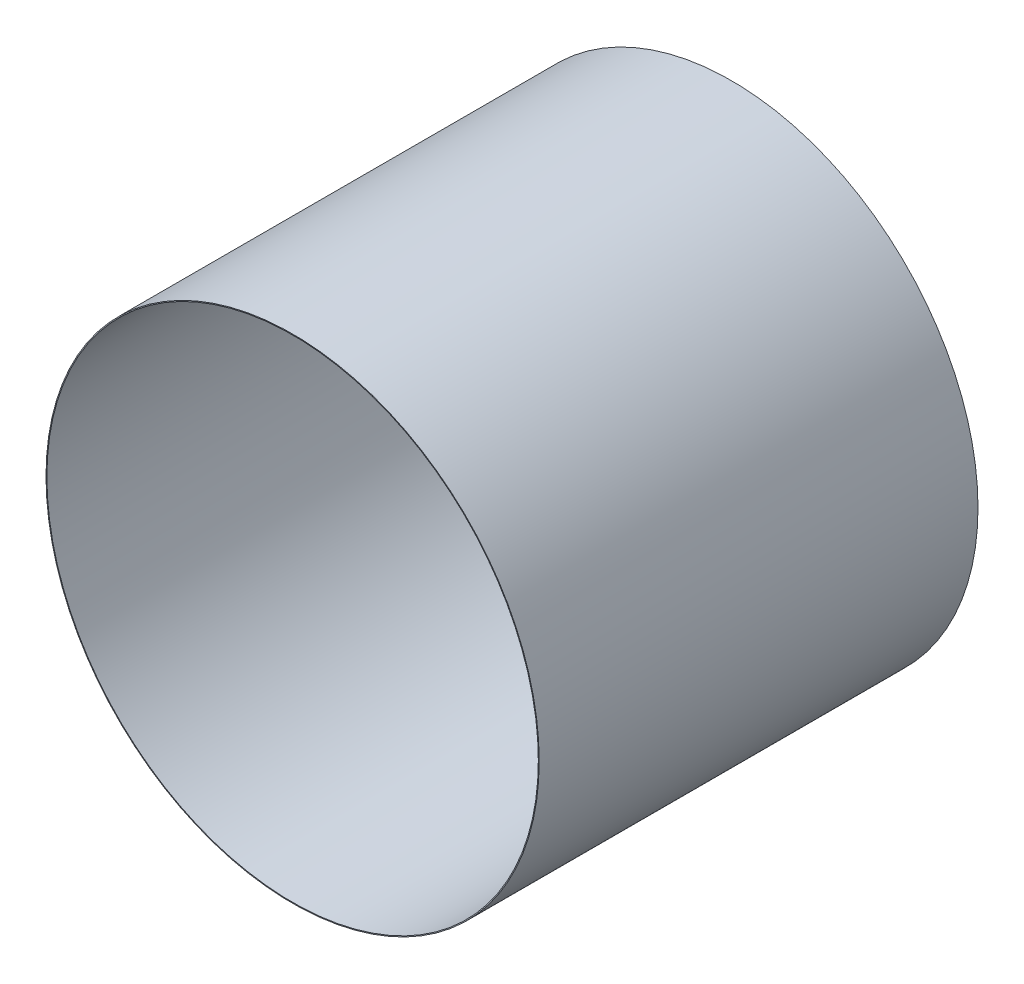
SolidWorks part; units mm, degrees
ref_plane "Front Plane" through (0, 0, 0) normal (0, 0, 1) x (1, 0, 0)
ref_plane "Top Plane" through (0, 0, 0) normal (0, 1, 0) x (1, 0, 0)
ref_plane "Right Plane" through (0, 0, 0) normal (1, 0, 0) x (0, 0, -1)
sketch "Sketch1" plane through (0, 0, 0) normal (0, 0, 1) x (1, 0, 0)
  circle A0 centre (0, 0) radius 14.05
  circle A1 centre (0, 0) radius 14
  dimension "D1" = 28
  dimension "D2" = 28.1
extrude "Boss-Extrude1" add sketch "Sketch1" along normal blind 25
